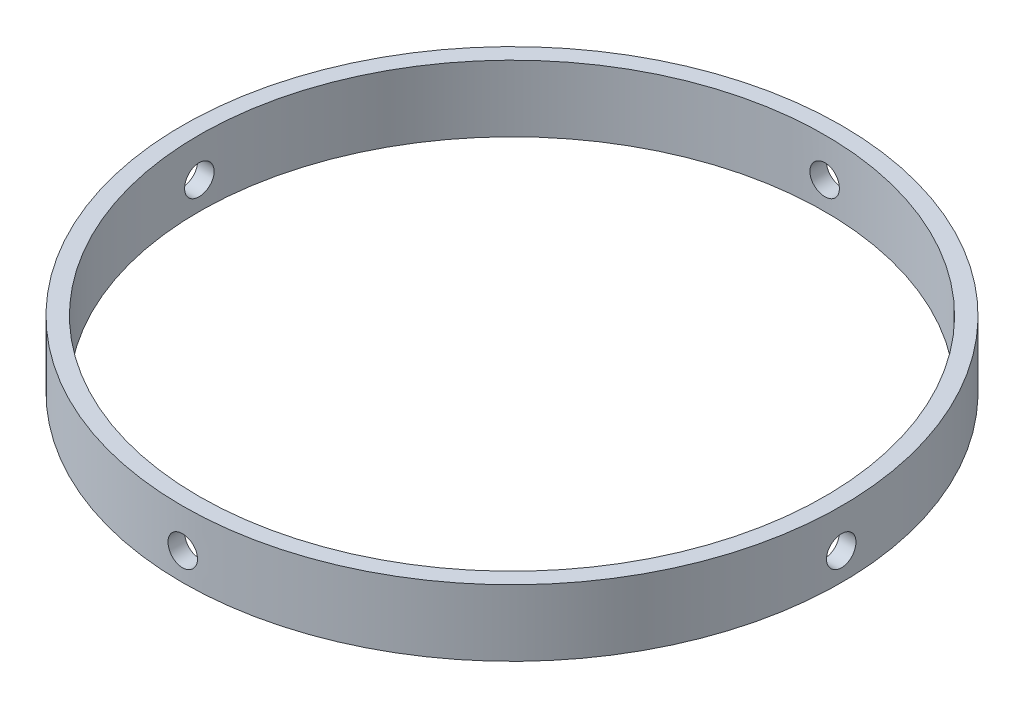
SolidWorks part; units mm, degrees
ref_plane "Front Plane" through (0, 0, 0) normal (0, 0, 1) x (1, 0, 0)
ref_plane "Top Plane" through (0, 0, 0) normal (0, 1, 0) x (1, 0, 0)
ref_plane "Right Plane" through (0, 0, 0) normal (1, 0, 0) x (0, 0, -1)
sketch "Sketch1" plane through (0, 0, 0) normal (0, 1, 0) x (1, 0, 0)
  circle A0 centre (0, 0) radius 37.846
  circle A4 centre (0, 0) radius 35.941
extrude "Boss-Extrude1" add sketch "Sketch1" along normal blind 7.62
sketch "Sketch2" plane through (0, 0, 0) normal (0, 0, 1) x (1, 0, 0)
  circle A0 centre (0, 3.171) radius 1.6929
extrude "Cut-Extrude1" cut sketch "Sketch2" along normal blind 86.62
pattern_circular "CirPattern1" count 4 over 360 about axis through (0, 7.62, 0) along (0, -1, 0) of "Cut-Extrude1"
